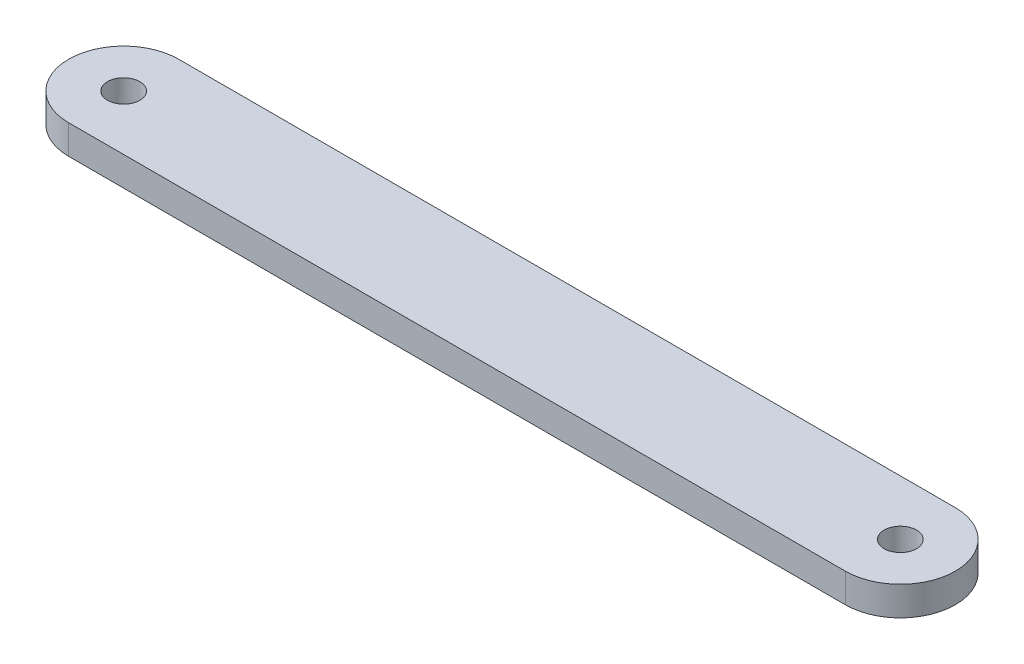
SolidWorks part; units mm, degrees
ref_plane "Front Plane" through (0, 0, 0) normal (0, 0, 1) x (1, 0, 0)
ref_plane "Top Plane" through (0, 0, 0) normal (0, 1, 0) x (1, 0, 0)
ref_plane "Right Plane" through (0, 0, 0) normal (1, 0, 0) x (0, 0, -1)
sketch "Sketch1" plane through (0, 0, 0) normal (0, 1, 0) x (1, 0, 0)
  line L1 (-120, 8.5) -> (0, 8.5)
  line L2 (-120, -8.5) -> (0, -8.5)
  circle A0 centre (0, 0) radius 2.5
  circle A1 centre (0, 0) radius 8.5
  circle A2 centre (-120, 0) radius 2.5
  circle A3 centre (-120, 0) radius 8.5
  dimension "D1" = 5
  dimension "D2" = 17
  dimension "D3" = 5
  dimension "D4" = 17
  dimension "D5" = 120
extrude "Boss-Extrude2" add sketch "Sketch1" along normal blind 4.5 contours A3 L2 A1 L1 | A3 A2 | A1 A0
